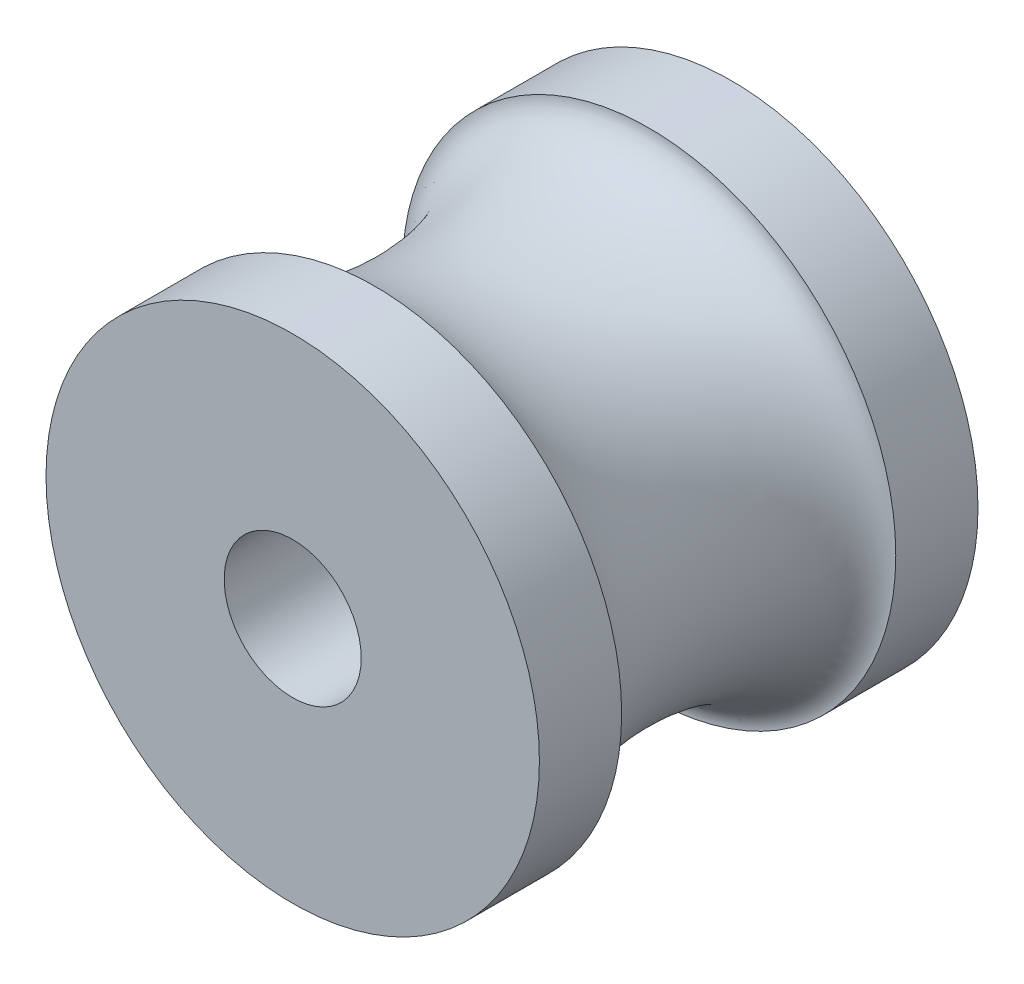
SolidWorks part; units mm, degrees
ref_plane "Front Plane" through (0, 0, 0) normal (0, 0, 1) x (1, 0, 0)
ref_plane "Top Plane" through (0, 0, 0) normal (0, 1, 0) x (1, 0, 0)
ref_plane "Right Plane" through (0, 0, 0) normal (1, 0, 0) x (0, 0, -1)
sketch "Sketch1" plane through (0, 0, 0) normal (0, 0, 1) x (1, 0, 0)
  circle A0 centre (0, 0) radius 9
  circle A1 centre (0, 0) radius 2.5
  dimension "D1" = 18
  dimension "D2" = 5
extrude "Boss-Extrude1" add sketch "Sketch1" along normal blind 16
sketch "Sketch2" plane through (0, 0, 0) normal (1, 0, 0) x (0, 0, -1)
  line L1 (0, 9) -> (-16, 9) construction
  line L2 (0, -9) -> (0, 9) construction
  line L3 (-16, 9) -> (-16, -9) construction
  ellipse E0 centre (-8, 9) end of major axis (-13, 9) minor radius 2
  point P12 (0, 0)
  point P13 (-8, 9)
sketch "Sketch3" plane through (0, 0, 0) normal (1, 0, 0) x (0, 0, -1)
  line L0 (0, 0) -> (-26.6894, 0) construction
revolve "Cut-Revolve1" cut sketch "Sketch2" angle 360 about L0
